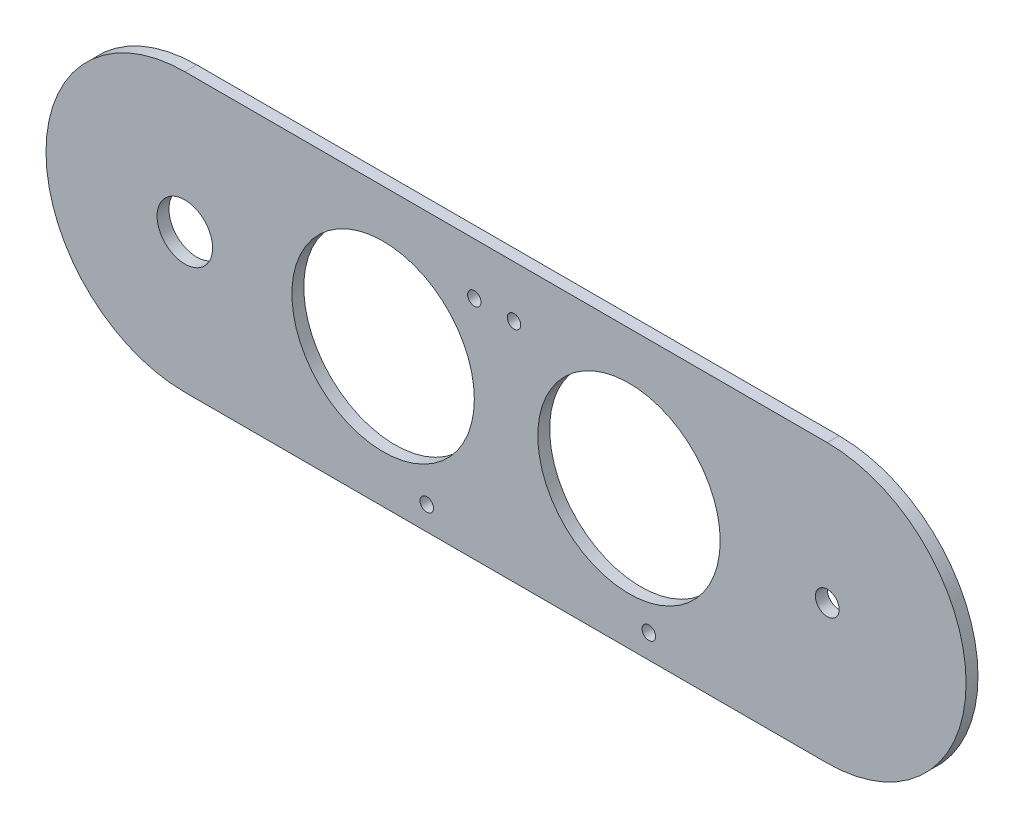
SolidWorks part; units mm, degrees
ref_plane "Plan1" through (0, 0, 0) normal (0, 0, 1) x (1, 0, 0)
ref_plane "Plan2" through (0, 0, 0) normal (0, 1, 0) x (1, 0, 0)
ref_plane "Plan3" through (0, 0, 0) normal (1, 0, 0) x (0, 0, -1)
sketch "Esquisse2" plane through (0, 0, 0) normal (0, 0, 1) x (1, 0, 0)
  line L0 (-60.5878, 50.043) -> (101.4122, 50.043)
  line L1 (-60.5878, -19.957) -> (101.4122, -19.957)
  line L2 (-60.5878, 15.043) -> (101.4122, 15.043) construction
  arc A0 (-60.5878, 50.043) -> (-60.5878, -19.957) centre (-60.5878, 15.043) ccw
  arc A1 (101.4122, 50.043) -> (101.4122, -19.957) centre (101.4122, 15.043) cw
  circle A2 centre (-60.5878, 15.043) radius 7
  circle A3 centre (101.4122, 15.043) radius 3
  circle A4 centre (51.4122, 15.043) radius 23
  circle A5 centre (-10.5878, 15.043) radius 23
  dimension "D2" = 35
  dimension "D5" = 46
  dimension "D6" = 46
  dimension "D7" = 6
  dimension "D8" = 14
  dimension "D1" = 162
  dimension "D3" = 50
  dimension "D4" = 62
extrude "Base-Extrusion" add sketch "Esquisse2" along normal blind 3
sketch "Esquisse9" plane through (0, 0, 3) normal (0, 0, 1) x (1, 0, 0)
  line L0 (-7.1251, 15.043) -> (51.4122, 15.043) construction
  circle A0 centre (12.4122, 37.043) radius 1.7
  dimension "D3" = 3.4
  dimension "D1" = 22
  dimension "D2" = 73
extrude "Enlèv. mat.-Extru.2" cut sketch "Esquisse9" against normal through all
pattern_linear "Répétition linéaire1" count 2 spacing 10
sketch "Esquisse10" plane through (0, 0, 3) normal (0, 0, 1) x (1, 0, 0)
  line L0 (48.4219, 15.043) -> (-10.5878, 15.043) construction
  circle A0 centre (0.4122, -13.957) radius 1.7
  dimension "D3" = 3.4
  dimension "D1" = 29
  dimension "D2" = 61
extrude "Enlèv. mat.-Extru.3" cut sketch "Esquisse10" against normal through all
pattern_linear "Répétition linéaire2" count 2 spacing 56
